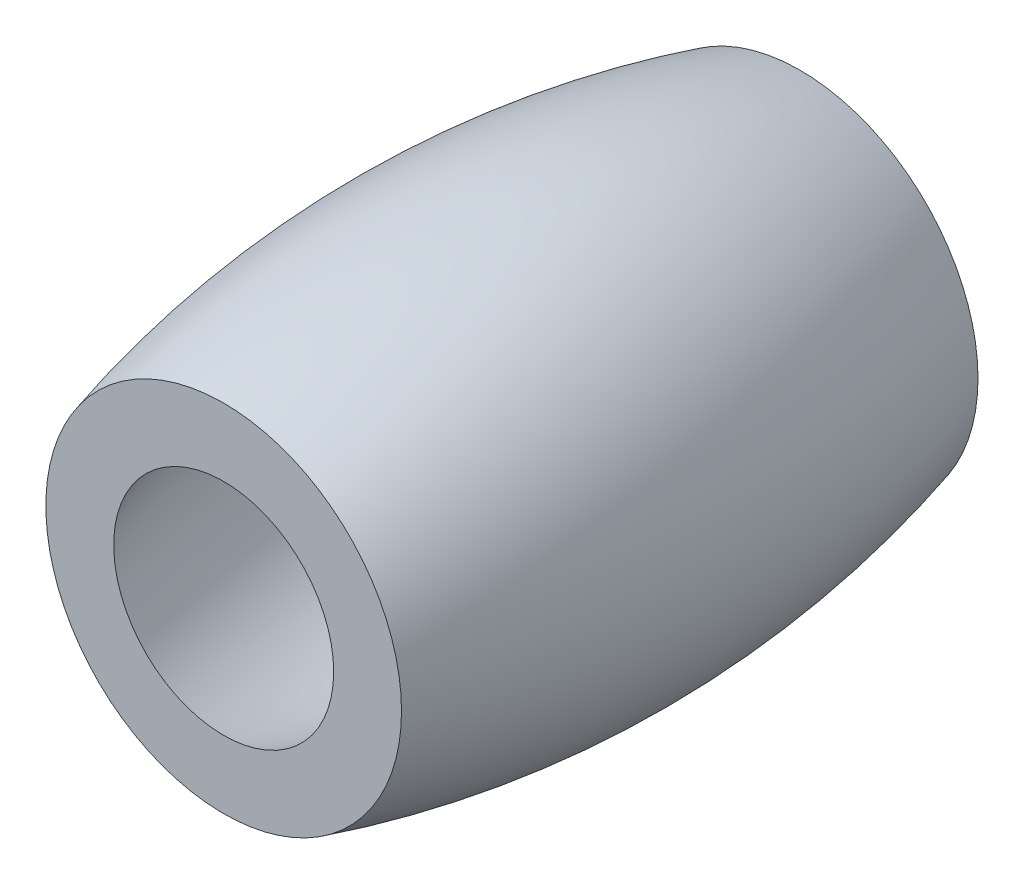
SolidWorks part; units mm, degrees
ref_plane "Front Plane" through (0, 0, 0) normal (0, 0, 1) x (1, 0, 0)
ref_plane "Top Plane" through (0, 0, 0) normal (0, 1, 0) x (1, 0, 0)
ref_plane "Right Plane" through (0, 0, 0) normal (1, 0, 0) x (0, 0, -1)
sketch "Sketch1" plane through (0, 0, 0) normal (1, 0, 0) x (0, 0, -1)
  line L0 (0, 0) -> (0, 31.83) construction
  line L1 (12.2305, 16.8762) -> (20.7305, 2.1538) construction
  line L2 (-8.5, 20.1859) -> (8.5, 20.1859) construction
  line L3 (-8.5, 20.1859) -> (-8.5, 30.6741) construction
  line L4 (-8.5, 30.6741) -> (8.5, 30.6741) construction
  line L5 (8.5, 20.1859) -> (8.5, 30.6741) construction
  line L6 (-8.5, 20.1859) -> (8.5, 30.6741) construction
  line L7 (-8.5, 30.6741) -> (8.5, 20.1859) construction
  line L8 (-8.5, 19.03) -> (8.5, 19.03) construction
  line L9 (-8.5, 19.03) -> (-8.5, 31.83) construction
  line L10 (-8.5, 31.83) -> (8.5, 31.83) construction
  line L11 (8.5, 19.03) -> (8.5, 31.83) construction
  line L12 (-8.5, 19.03) -> (8.5, 31.83) construction
  line L13 (-8.5, 31.83) -> (8.5, 19.03) construction
  line L14 (23.3156, 23.2762) -> (31.8156, 8.5538) construction
  line L15 (20.7305, 2.1538) -> (31.8156, 8.5538) construction
  line L16 (12.2305, 16.8762) -> (23.3156, 23.2762) construction
  line L17 (20.7305, -2.1538) -> (12.2305, -16.8762) construction
  line L18 (31.8156, -8.5538) -> (23.3156, -23.2762) construction
  line L19 (12.2305, -16.8762) -> (23.3156, -23.2762) construction
  line L20 (20.7305, -2.1538) -> (31.8156, -8.5538) construction
  line L21 (8.5, -19.03) -> (-8.5, -19.03) construction
  line L22 (8.5, -31.83) -> (-8.5, -31.83) construction
  line L23 (-8.5, -19.03) -> (-8.5, -31.83) construction
  line L24 (8.5, -19.03) -> (8.5, -31.83) construction
  line L25 (-12.2305, -16.8762) -> (-20.7305, -2.1538) construction
  line L26 (-23.3156, -23.2762) -> (-31.8156, -8.5538) construction
  line L27 (-20.7305, -2.1538) -> (-31.8156, -8.5538) construction
  line L28 (-12.2305, -16.8762) -> (-23.3156, -23.2762) construction
  line L29 (-20.7305, 2.1538) -> (-12.2305, 16.8762) construction
  line L30 (-31.8156, 8.5538) -> (-23.3156, 23.2762) construction
  line L31 (-12.2305, 16.8762) -> (-23.3156, 23.2762) construction
  line L32 (-20.7305, 2.1538) -> (-31.8156, 8.5538) construction
  line L36 (-8.5, 28.6741) -> (8.5, 28.6741) construction
  line L37 (-8.5, 28.6741) -> (-8.5, 30.6741)
  line L38 (8.5, 30.6741) -> (8.5, 28.6741)
  line L39 (0, 25.43) -> (11.8986, 25.43) construction
  circle A0 centre (0, 0) radius 31.83 construction
  arc A1 (-8.5, 30.6741) -> (8.5, 30.6741) centre (0, 0) cw
  arc A2 (-8.5, 28.6741) -> (8.5, 28.6741) centre (0, -2) cw
  point P3 (0, 25.43)
  point P9 (0, 25.43)
  point P36 (0, 0)
  dimension "D1" = 63.66
  dimension "D2" = 17
  dimension "D3" = 12.8
  dimension "D5" = 2
  dimension "D6" = 8.8
  dimension "D7" = 6.4882
  dimension "D4" = 6
revolve "Revolve1" add sketch "Sketch1" angle 360 about L39
